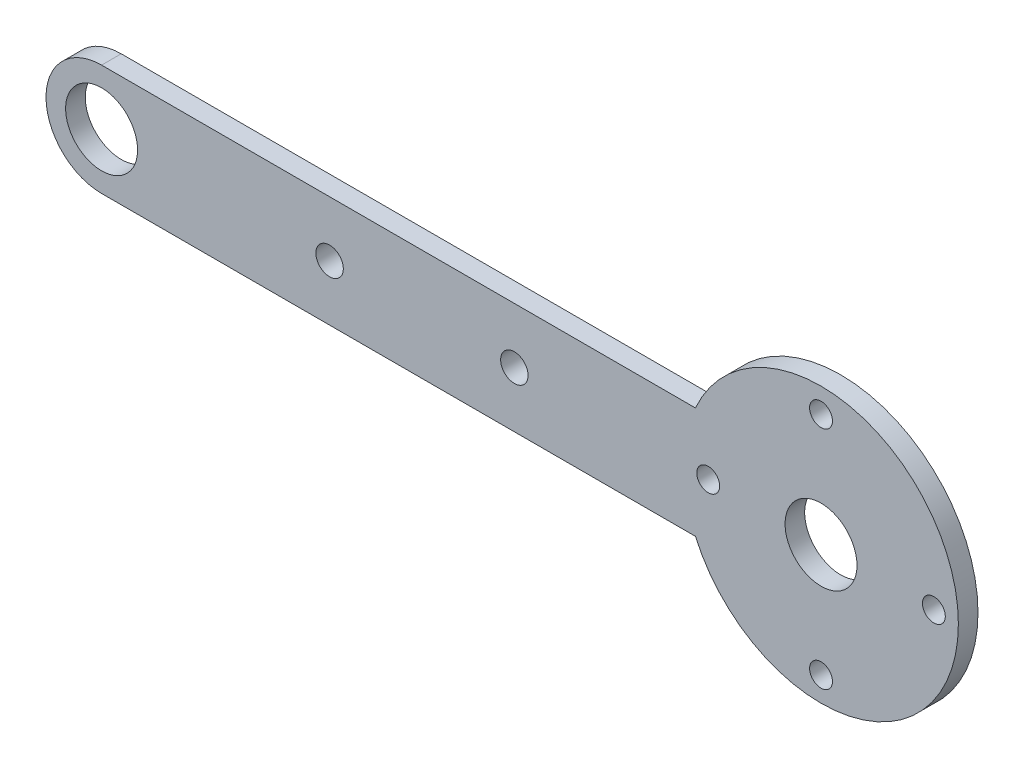
SolidWorks part; units mm, degrees
ref_plane "Plan de face" through (0, 0, 0) normal (0, 0, 1) x (1, 0, 0)
ref_plane "Plan de dessus" through (0, 0, 0) normal (0, 1, 0) x (1, 0, 0)
ref_plane "Plan de droite" through (0, 0, 0) normal (1, 0, 0) x (0, 0, -1)
sketch "Esquisse1" plane through (0, 0, 0) normal (0, 0, 1) x (1, 0, 0)
  line L0 (-110, 8.5) -> (-19.2029, 8.5)
  line L1 (-110, -8.5) -> (-19.2029, -8.5)
  line L2 (-17.25, 0) -> (0, 17.25) construction
  line L3 (0, 17.25) -> (17.25, 0) construction
  line L4 (17.25, 0) -> (0, -17.25) construction
  line L5 (0, -17.25) -> (-17.25, 0) construction
  line L6 (0, 17.25) -> (0, 0) construction
  line L7 (0, 0) -> (0, -17.25) construction
  line L8 (-17.25, 0) -> (0, 0) construction
  line L9 (0, 0) -> (17.25, 0) construction
  arc A0 (-19.2029, -8.5) -> (-19.2029, 8.5) centre (0, 0) ccw
  arc A1 (-110, 8.5) -> (-110, -8.5) centre (-110, 0) ccw
  circle A2 centre (-110, 0) radius 5.5
  circle A3 centre (0, 0) radius 5.5
  circle A4 centre (0, 17.25) radius 1.75
  circle A5 centre (17.25, 0) radius 1.75
  circle A6 centre (0, -17.25) radius 1.75
  circle A7 centre (-17.25, 0) radius 1.75
  circle A8 centre (-75.14, 0) radius 2.1
  circle A9 centre (-46.89, 0) radius 2.1
  point P9 (-110, 5.5)
  dimension "D1" = 11
  dimension "D2" = 21
  dimension "D5" = 3.5
  dimension "D7" = 4.2
  dimension "D3" = 110
  dimension "D4" = 3
  dimension "D6" = 17.25
  dimension "D8" = 28.25
  dimension "D9" = 34.86
extrude "Boss.-Extru.1" add sketch "Esquisse1" along normal blind 3
